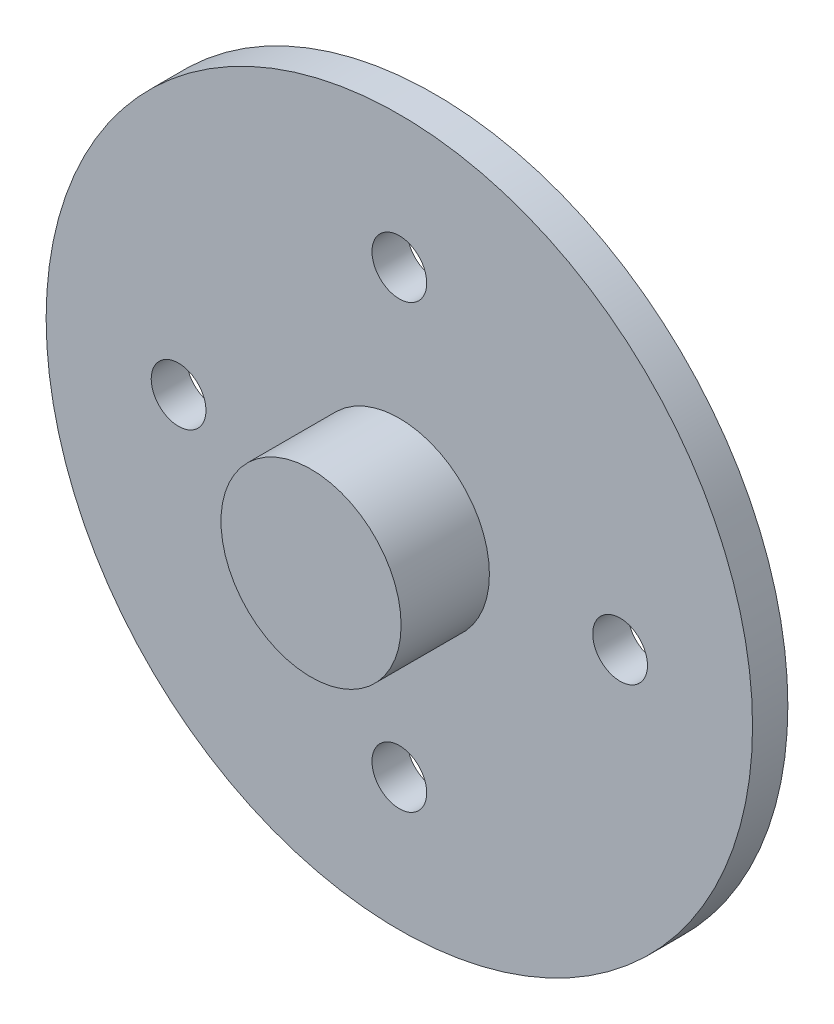
SolidWorks part; units mm, degrees
ref_plane "Plano frontal" through (0, 0, 0) normal (0, 0, 1) x (1, 0, 0)
ref_plane "Plano superior" through (0, 0, 0) normal (0, 1, 0) x (1, 0, 0)
ref_plane "Plano direito" through (0, 0, 0) normal (1, 0, 0) x (0, 0, -1)
sketch "Esboço1" plane through (0, 0, 0) normal (0, 0, 1) x (1, 0, 0)
  circle A0 centre (0, 0) radius 20
  dimension "D1" = 40
extrude "Ressalto-extrusão1" add sketch "Esboço1" along normal blind 2
sketch "Esboço2" plane through (0, 0, 2) normal (0, 0, 1) x (1, 0, 0)
  circle A0 centre (0, 0) radius 5.1
  dimension "D1" = 10.2
extrude "Ressalto-extrusão2" add sketch "Esboço2" along normal blind 5
sketch "Esboço3" plane through (0, 0, 2) normal (0, 0, 1) x (1, 0, 0)
  line L0 (0, 0) -> (12.5, 0) construction
  circle A0 centre (12.5, 0) radius 1.55
  point P3 (13.4975, 0)
  dimension "D1" = 3.1
  dimension "D2" = 12.5
extrude "Corte-extrusão1" cut sketch "Esboço3" against normal through all
pattern_circular "PadrãoCircular1" count 4 over 360 about axis through (0, 0, 0) along (0, 0, 1) of "Corte-extrusão1"
